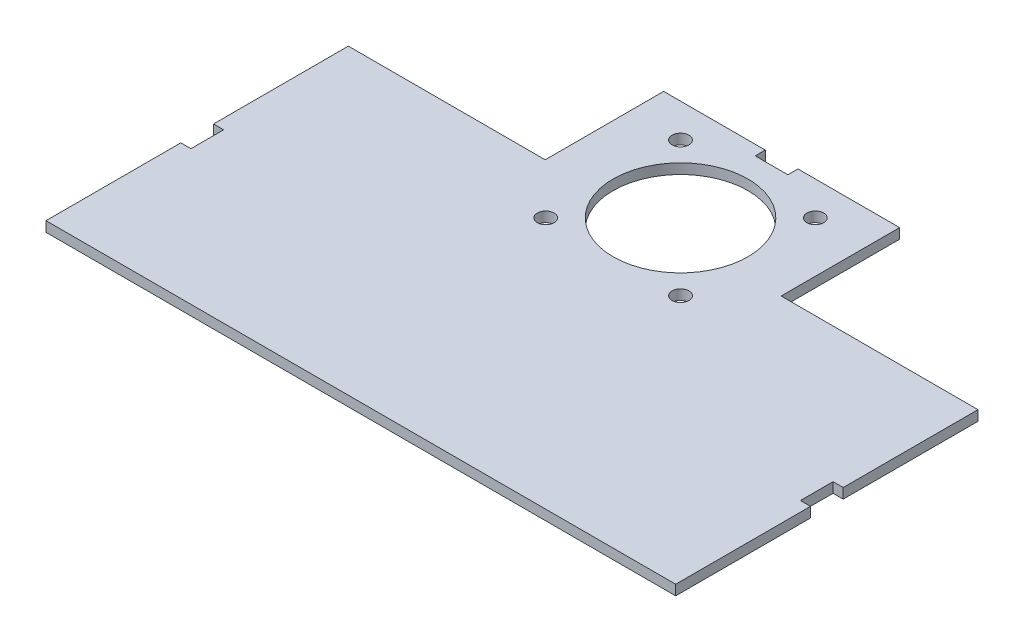
SolidWorks part; units mm, degrees
material "3mm Birch Ply Wood"
ref_plane "Front Plane" through (0, 0, 0) normal (0, 0, 1) x (1, 0, 0)
ref_plane "Top Plane" through (0, 0, 0) normal (0, 1, 0) x (1, 0, 0)
ref_plane "Right Plane" through (0, 0, 0) normal (1, 0, 0) x (0, 0, -1)
sketch "Sketch1" plane through (0, 0, 0) normal (0, 1, 0) x (1, 0, 0)
  line L0 (-148.2884, -111.3091) -> (-148.2884, -101.6091)
  line L2 (-22.8784, -26.4591) -> (-53.0284, -26.4591)
  line L3 (-148.2884, -101.6091) -> (-151.2884, -101.6091)
  line L4 (-92.8784, -26.4591) -> (-92.8784, -61.6091)
  line L5 (-151.2884, -101.6091) -> (-151.2884, -61.6091)
  line L6 (-151.2884, -61.6091) -> (-92.8784, -61.6091)
  line L7 (35.5316, -61.6091) -> (35.5316, -101.6091)
  line L8 (-22.8784, -26.4591) -> (-22.8784, -61.6091)
  line L9 (35.5316, -101.6091) -> (32.5316, -101.6091)
  line L10 (-22.8784, -61.6091) -> (35.5316, -61.6091)
  line L11 (32.5316, -101.6091) -> (32.5316, -111.3091)
  line L12 (-148.2884, -106.4591) -> (32.5316, -106.4591) construction
  line L13 (35.5316, -111.3091) -> (32.5316, -111.3091)
  line L14 (35.5316, -151.3091) -> (35.5316, -111.3091)
  line L15 (-151.2884, -151.3091) -> (35.5316, -151.3091)
  line L16 (-151.2884, -111.3091) -> (-151.2884, -151.3091)
  line L17 (-148.2884, -111.3091) -> (-151.2884, -111.3091)
  line L18 (-62.7284, -29.4591) -> (-53.0284, -29.4591)
  line L19 (-53.0284, -29.4591) -> (-53.0284, -26.4591)
  line L20 (-62.7284, -29.4591) -> (-62.7284, -26.4591)
  line L21 (-62.7284, -26.4591) -> (-92.8784, -26.4591)
  point P17 (-57.8784, -29.4591)
extrude "Boss-Extrude1" add sketch "Sketch1" along normal blind 3
sketch "Sketch3" plane through (0, 3, 0) normal (0, 1, 0) x (1, 0, 0)
  line L0 (-92.8784, -26.4591) -> (-92.8784, -36.4591) construction
  line L1 (-92.8784, -26.4591) -> (-92.8784, -61.6091) construction
  line L2 (-92.8784, -36.4591) -> (-77.8784, -36.4591) construction
  line L3 (-57.8784, -29.4591) -> (-57.8784, -47.8051) construction
  line L4 (-53.0284, -29.4591) -> (-62.7284, -29.4591) construction
  line L5 (-22.8784, -36.4591) -> (-37.8784, -36.4591) construction
  line L6 (-22.8784, -26.4591) -> (-22.8784, -36.4591) construction
  line L7 (-77.8784, -36.4591) -> (-77.8784, -76.4591) construction
  line L8 (-77.8784, -56.4591) -> (-27.8784, -56.4591) construction
  line L9 (-77.8784, -36.4591) -> (-37.8784, -76.4591) construction
  line L10 (-37.8784, -76.4591) -> (-37.8784, -36.4591) construction
  line L11 (-37.8784, -36.4591) -> (-77.8784, -76.4591) construction
  circle A0 centre (-77.8784, -36.4591) radius 2.5
  circle A1 centre (-37.8784, -36.4591) radius 2.5
  circle A2 centre (-37.8784, -76.4591) radius 2.5
  circle A3 centre (-77.8784, -76.4591) radius 2.5
  circle A4 centre (-57.8784, -56.4591) radius 20
extrude "Cut-Extrude1" cut sketch "Sketch3" against normal blind 10
